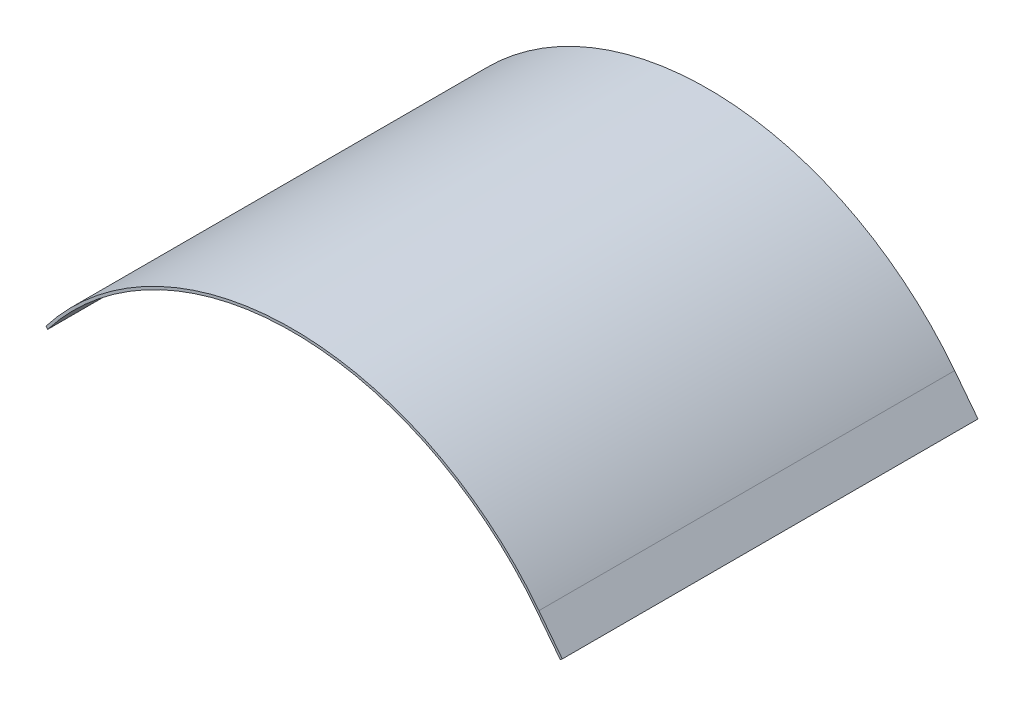
SolidWorks part; units mm, degrees
ref_plane "Front Plane" through (0, 0, 0) normal (0, 0, 1) x (1, 0, 0)
ref_plane "Top Plane" through (0, 0, 0) normal (0, 1, 0) x (1, 0, 0)
ref_plane "Right Plane" through (0, 0, 0) normal (1, 0, 0) x (0, 0, -1)
sketch "Sketch1" plane through (0, 0, 0) normal (0, 0, 1) x (1, 0, 0)
  line L0 (1897.37, 0) -> (1987.3089, -116.1111)
  line L1 (1889.4643, -6.1237) -> (1979.4032, -122.2348)
  line L2 (1987.3089, -116.1111) -> (1979.4032, -122.2348)
  line L3 (0, 0) -> (6.3263, -8.1673)
  line L4 (7.9057, -6.1237) -> (6.3263, -8.1673)
  arc A0 (0, 0) -> (1897.37, 0) centre (948.685, -734.8447) cw
  arc A1 (7.9057, -6.1237) -> (1889.4643, -6.1237) centre (948.685, -734.8447) cw
  dimension "D1" = 1200
  dimension "D2" = 1897.37
  dimension "D3" = 146.87
  dimension "D4" = 10
extrude "Boss-Extrude1" add sketch "Sketch1" along normal blind 1600 contours A0 L0 L2 L1 A1 L4 L3
